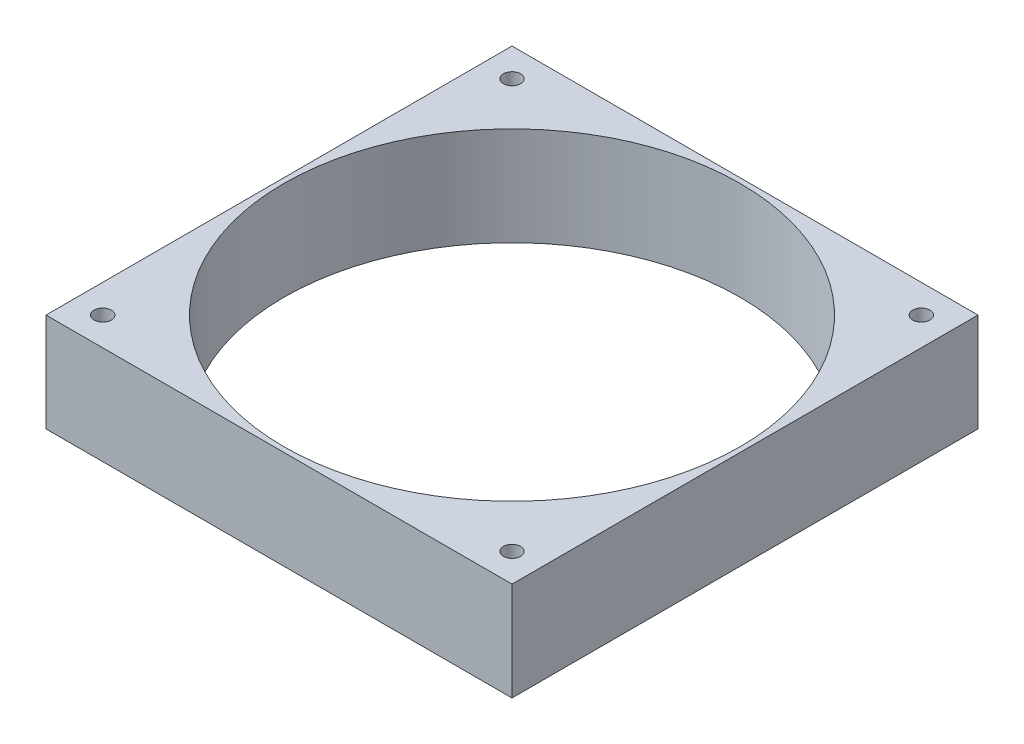
SolidWorks part; units mm, degrees
ref_plane "Front Plane" through (0, 0, 0) normal (0, 0, 1) x (1, 0, 0)
ref_plane "Top Plane" through (0, 0, 0) normal (0, 1, 0) x (1, 0, 0)
ref_plane "Right Plane" through (0, 0, 0) normal (1, 0, 0) x (0, 0, -1)
sketch "Sketch1" plane through (0, 0, 0) normal (0, 1, 0) x (1, 0, 0)
  line L0 (-60.0075, 0) -> (60.0075, 0) construction
  line L1 (-60.0075, -60.0075) -> (60.0075, -60.0075)
  line L2 (-60.0075, -60.0075) -> (-60.0075, 60.0075)
  line L3 (-60.0075, 60.0075) -> (60.0075, 60.0075)
  line L4 (60.0075, -60.0075) -> (60.0075, 60.0075)
  line L5 (-60.0075, -60.0075) -> (60.0075, 60.0075) construction
  line L6 (-60.0075, 60.0075) -> (60.0075, -60.0075) construction
  circle A0 centre (-52.705, 52.705) radius 2.2225
  circle A1 centre (52.705, -52.705) radius 2.2225
  circle A2 centre (52.705, 52.705) radius 2.2225
  circle A3 centre (-52.705, -52.705) radius 2.2225
  point P0 (0, 0)
  point P8 (-52.705, 54.9275)
  dimension "D2" = 4.445
  dimension "D1" = 120.015
  dimension "D3" = 5.08
extrude "Boss-Extrude1" add sketch "Sketch1" along normal blind 25.4
sketch "Sketch2" plane through (0, 25.4, 0) normal (0, 1, 0) x (1, 0, 0)
  line L0 (-60.0075, 60.0075) -> (60.0075, -60.0075) construction
  circle A0 centre (0, 0) radius 58.7375
  dimension "D1" = 117.475
extrude "Cut-Extrude1" cut sketch "Sketch2" against normal through all
